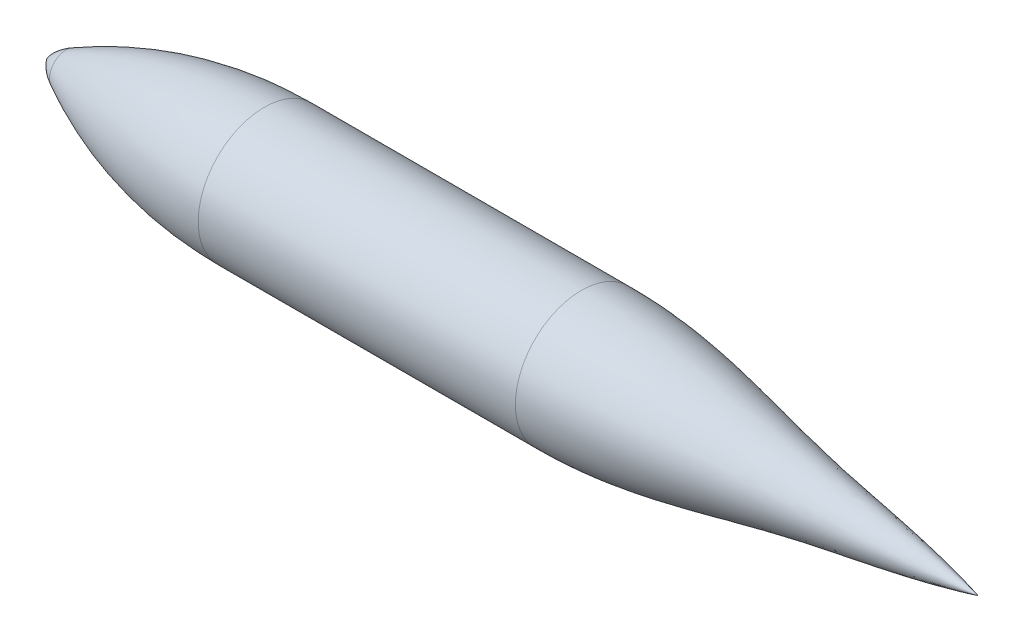
SolidWorks part; units mm, degrees
material "3003-H14"
ref_plane "Piano frontale" through (0, 0, 0) normal (1, 0, 0) x (0, 1, 0)
ref_plane "Piano superiore" through (0, 0, 0) normal (0, 0, 1) x (0, 1, 0)
ref_plane "Piano destro" through (0, 0, 0) normal (0, 1, 0) x (-1, 0, 0)
sketch "Schizzo6" plane through (0, 0, 0) normal (0, 1, 0) x (-1, 0, 0)
  line L0 (312.8, 28.97) -> (173.8, 28.97)
  line L1 (0, 0) -> (407.9842, 0)
  spline S0 degree 2 poles (312.8, 28.97) (358.929, 28.7786) (399.7, 7.24) knots 0 0 0 1 1 1
  spline S1 degree 2 poles (399.7, 7.24) (404.7781, 4.6847) (407.9842, 0) knots 0 0 0 1 1 1
  spline S2 degree 3 poles (0, 0) (25.1897, 6.7516) (65.5245, 11.0779) (123.6018, 24.779) (154.2741, 28.97) (173.8, 28.97) knots 0 0 0 0 0.440523 0.69482 1 1 1 1
  point P0 (0, 0)
  point P1 (312.8, 28.97)
  point P3 (173.8, 28.97)
  point P4 (399.7, 7.24)
  dimension "D1" = 173.8
  dimension "D2" = 399.7
  dimension "D3" = 312.8
  dimension "D4" = 28.97
  dimension "D5" = 7.24
  dimension "D6" = 28.97
revolve "Rivoluzione1" add sketch "Schizzo6" angle 360 about L1
equation "\"D\"= 182 / pi"
equation "\"R\"= \"D\" / 2"
equation "\"NoseRatio\"= 3"
equation "\"L_cyl\" = 139"
equation "\"L_nose\"= \"NoseRatio\" * \"D\""
equation "\"L_total\"= \"L_nose\" + \"L_cyl\""
equation "\"TailRatio\"= 1.5"
equation "\"L_tail\"= \"TailRatio\" * \"D\""
equation "\"R_tip\"= 0.03 * \"D\""
